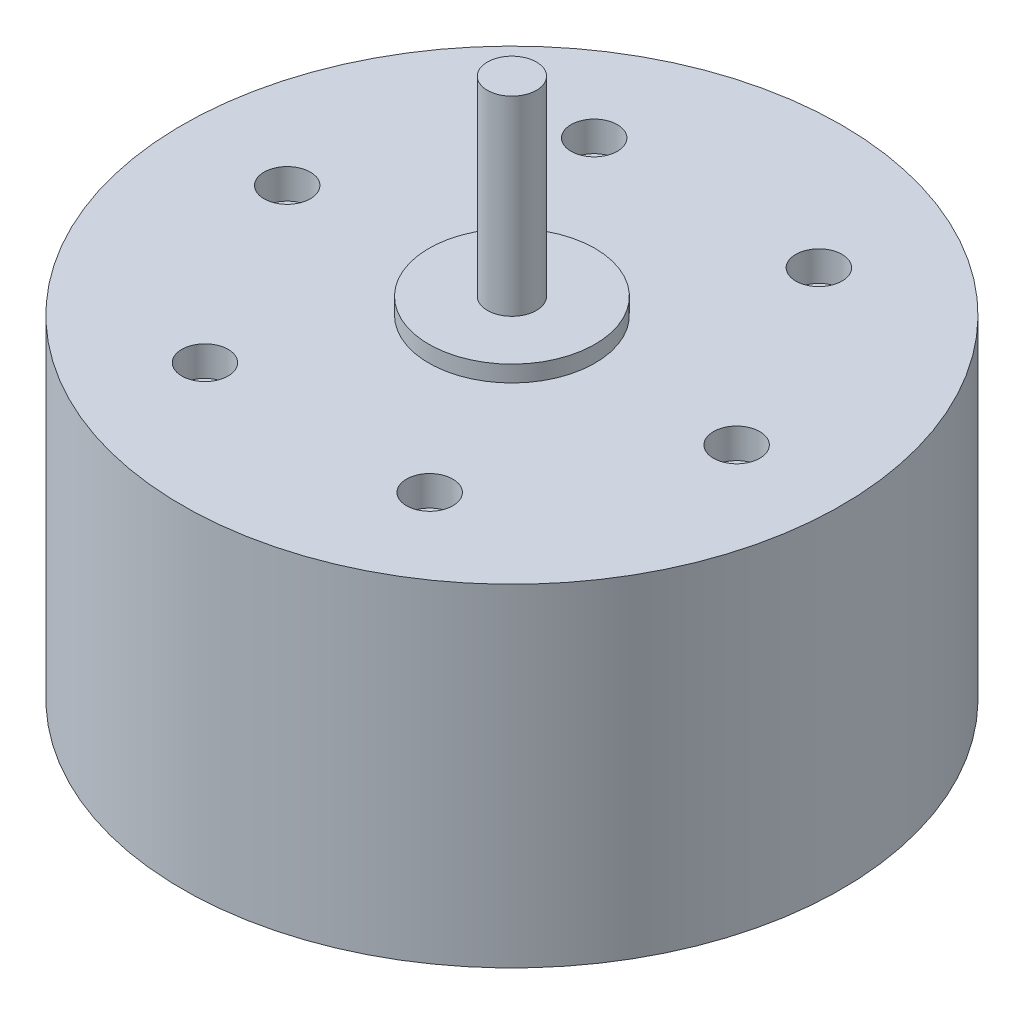
SolidWorks part; units mm, degrees
ref_plane "Front Plane" through (0, 0, 0) normal (0, 0, 1) x (1, 0, 0)
ref_plane "Top Plane" through (0, 0, 0) normal (0, 1, 0) x (1, 0, 0)
ref_plane "Right Plane" through (0, 0, 0) normal (1, 0, 0) x (0, 0, -1)
sketch "Sketch1" plane through (0, 0, 0) normal (0, 0, 1) x (1, 0, 0)
  line L0 (0, -11.8432) -> (0, 9.225) construction
  line L1 (0, -10.15) -> (0, 10.15)
  line L2 (0, 10.15) -> (0.9, 10.15)
  line L3 (0.9, 10.15) -> (0.9, 3.15)
  line L4 (0.9, 3.15) -> (3.05, 3.15)
  line L5 (3.05, 3.15) -> (3.05, 2.55)
  line L6 (3.05, 2.55) -> (12.1, 2.55)
  line L7 (12.1, 2.55) -> (12.1, -9.65)
  line L8 (12.1, -9.65) -> (11.9, -9.65)
  line L9 (11.9, -9.65) -> (11.9, -9.05)
  line L10 (11.9, -9.05) -> (2.85, -9.05)
  line L11 (2.85, -9.05) -> (2.85, -10.15)
  line L12 (2.85, -10.15) -> (0, -10.15)
  point P5 (0.9, 14.0816)
  point P16 (2.85, -5.8433)
  point P17 (0.9, 3.15)
  point P18 (3.05, 2.5812)
  dimension "D1" = 1.8
  dimension "D2" = 6.1
  dimension "D3" = 24.2
  dimension "D4" = 5.7
  dimension "D5" = 0.2
  dimension "D6" = 7
  dimension "D7" = 0.6
  dimension "D8" = 12.2
  dimension "D9" = 0.6
  dimension "D10" = 1.1
revolve "Revolve1" add sketch "Sketch1" angle 360 about L0
sketch "Sketch2" plane through (0, 2.55, 0) normal (0, 1, 0) x (1, 0, 0)
  circle A0 centre (-8.25, 0) radius 0.85
  circle A1 centre (-4.125, 7.1447) radius 0.85
  circle A2 centre (4.125, 7.1447) radius 0.85
  circle A3 centre (8.25, 0) radius 0.85
  circle A4 centre (4.125, -7.1447) radius 0.85
  circle A5 centre (-4.125, -7.1447) radius 0.85
  point P3 (0, 0)
  point P4 (0, 0)
  point P14 (0, 0)
  point P16 (0, 0)
  dimension "D2" = 1.7
  dimension "D3" = 16.5
  dimension "D1" = 6
extrude "Cut-Extrude1" cut sketch "Sketch2" against normal blind 1.1
